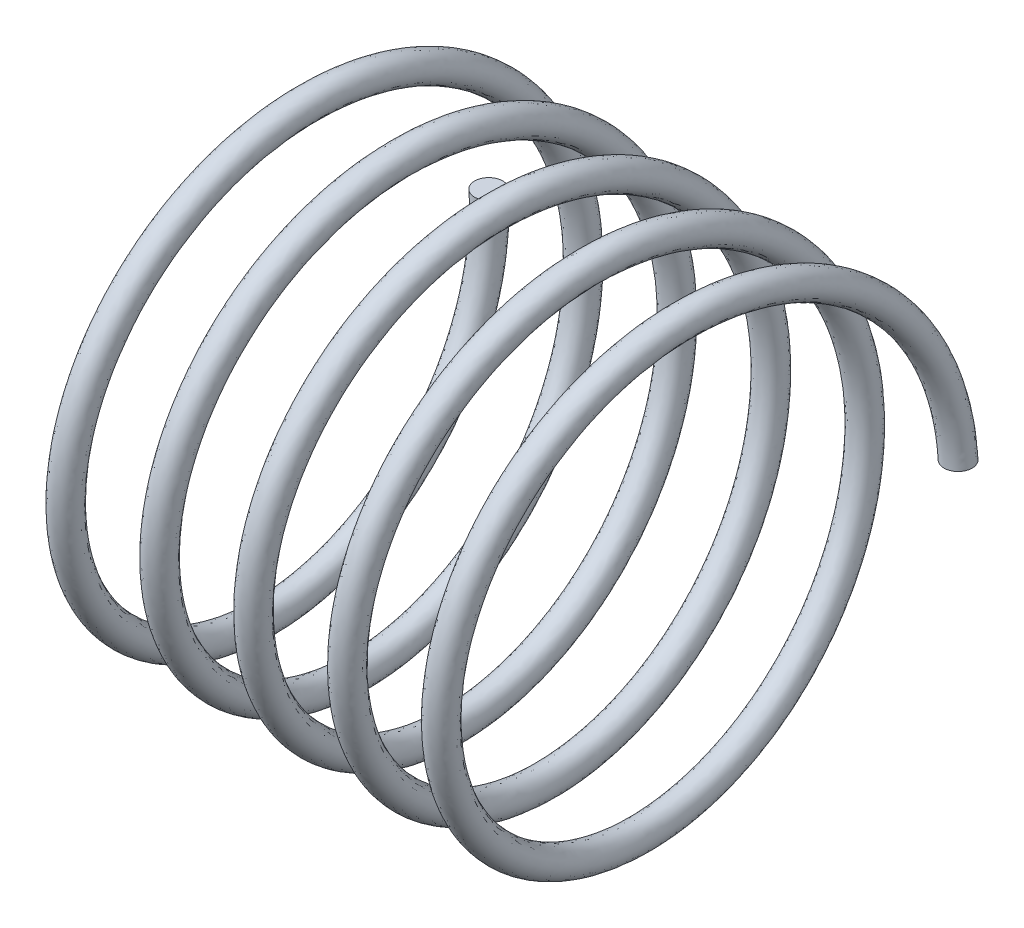
SolidWorks part; units mm, degrees
material "1023 Carbon Steel Sheet (SS)"
ref_plane "Front Plane" through (0, 0, 0) normal (0, 0, 1) x (1, 0, 0)
ref_plane "Top Plane" through (0, 0, 0) normal (0, 1, 0) x (1, 0, 0)
ref_plane "Right Plane" through (0, 0, 0) normal (1, 0, 0) x (0, 0, -1)
sketch "Sketch4" plane through (0, 0, 0) normal (1, 0, 0) x (0, 0, -1)
  circle A0 centre (0, 0) radius 25
  dimension "D1" = 50
curve "Helix/Spiral2" pitch 10 height 50 turns 5
sketch "Sketch5" plane through (0, 0, 0) normal (0, 1, 0) x (1, 0, 0)
  circle A0 centre (50, 25) radius 1.5
  point P2 (0, 0)
  dimension "D1" = 3
sweep "Sweep1" add profiles "Sketch5" path "Helix/Spiral2"
